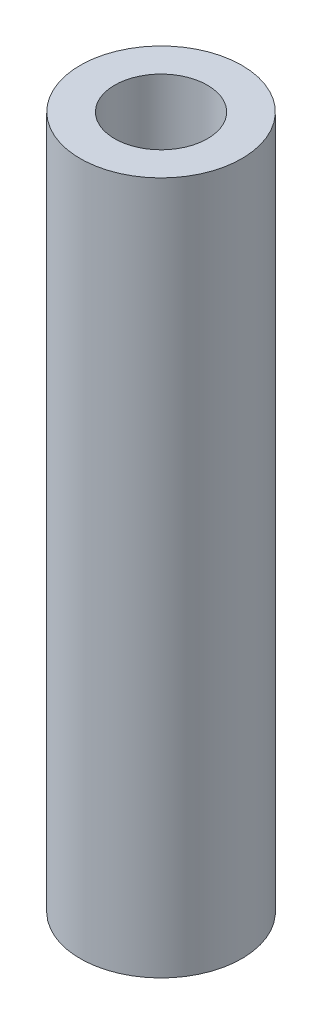
SolidWorks part; units mm, degrees
ref_plane "Front Plane" through (0, 0, 0) normal (0, 0, 1) x (1, 0, 0)
ref_plane "Top Plane" through (0, 0, 0) normal (0, 1, 0) x (1, 0, 0)
ref_plane "Right Plane" through (0, 0, 0) normal (1, 0, 0) x (0, 0, -1)
sketch "Sketch1" plane through (0, 0, 0) normal (0, 1, 0) x (1, 0, 0)
  circle A0 centre (0, 0) radius 2.5527
  circle A1 centre (0, 0) radius 4.445
  dimension "D1" = 5.1054
  dimension "D2" = 8.89
extrude "Boss-Extrude1" add sketch "Sketch1" along normal blind 38.1
